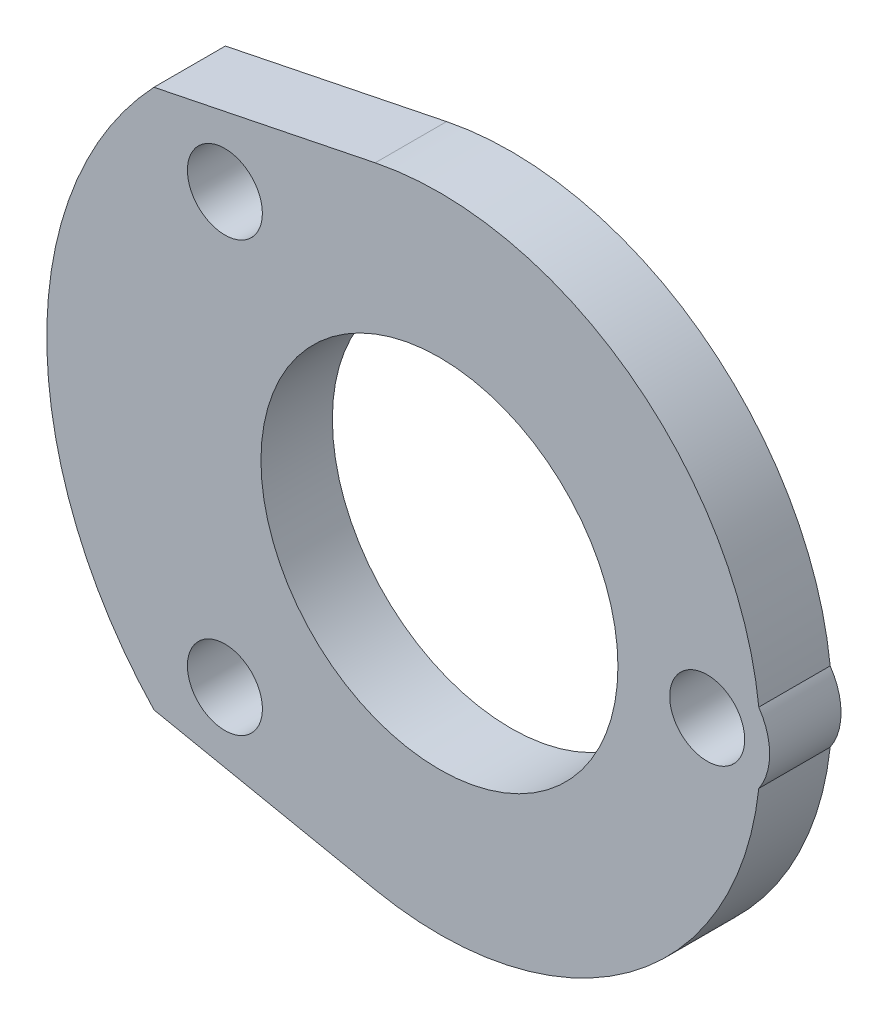
SolidWorks part; units mm, degrees
ref_plane "Plan de face" through (0, 0, 0) normal (0, 0, 1) x (1, 0, 0)
ref_plane "Plan de dessus" through (0, 0, 0) normal (0, 1, 0) x (1, 0, 0)
ref_plane "Plan de droite" through (0, 0, 0) normal (1, 0, 0) x (0, 0, -1)
sketch "Esquisse1" plane through (0, 0, 0) normal (0, 0, 1) x (1, 0, 0)
  line L0 (-14.6605, 0) -> (34.9686, 0) construction
  line L1 (0, 16.7007) -> (0, -12.5528) construction
  line L2 (-21, 4.899) -> (-1.8, 8.8182) construction
  line L3 (-21, -4.899) -> (-1.8, -8.8182) construction
  line L4 (-1.8, 5.9787) -> (-1.8, -15.8699) construction
  line L5 (0, 0) -> (-9.0228, 9.0228) construction
  line L6 (-7.9968, 7.5533) -> (-1.8, 8.8182)
  line L7 (-7.9968, -7.5533) -> (-1.8, -8.8182)
  circle A0 centre (0, 0) radius 5
  circle A1 centre (0, 0) radius 9 construction
  circle A2 centre (-20, 0) radius 5 construction
  arc A4 (-21, 4.899) -> (-21, -4.899) centre (-20, 0) ccw construction
  arc A6 (-1.8, 8.8182) -> (8.9458, 0.9859) centre (0, 0) cw
  arc A7 (-1.8, -8.8182) -> (8.9458, -0.9859) centre (0, 0) ccw
  arc A12 (-7.9968, 7.5533) -> (-7.9968, -7.5533) centre (0, 0) ccw
  circle A13 centre (7.5, 0) radius 1.75 construction
  arc A14 (8.9458, 0.9859) -> (8.9458, -0.9859) centre (7.5, 0) cw
  circle A16 centre (7.5, 0) radius 1.05
  circle A17 centre (0, 0) radius 8.5 construction
  circle A18 centre (-6.0104, 6.0104) radius 1.05
  circle A19 centre (-6.0104, -6.0104) radius 1.05
  dimension "D1" = 10
  dimension "D2" = 18
  dimension "D3" = 10
  dimension "D4" = 45
  dimension "D6" = 3.5
  dimension "D7" = 7.5
  dimension "D8" = 11
  dimension "D9" = 2.1
  dimension "D10" = 17
  dimension "D5" = 20
extrude "Boss.-Extru.1" add sketch "Esquisse1" along normal blind 2
